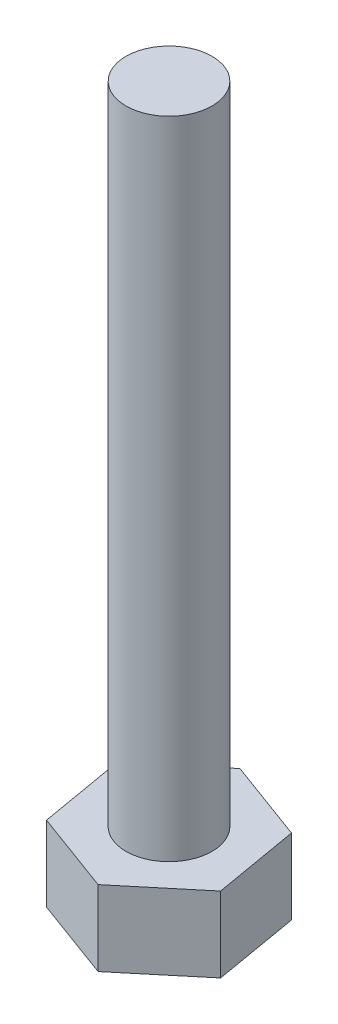
SolidWorks part; units mm, degrees
ref_plane "Спереди" through (0, 0, 0) normal (0, 0, 1) x (1, 0, 0)
ref_plane "Сверху" through (0, 0, 0) normal (0, 1, 0) x (1, 0, 0)
ref_plane "Справа" through (0, 0, 0) normal (1, 0, 0) x (0, 0, -1)
sketch "Эскиз1" plane through (0, 0, 0) normal (0, 1, 0) x (1, 0, 0)
  line L1 (3.7929, -1.3953) -> (3.1049, 2.5871)
  line L2 (3.1049, 2.5871) -> (-0.6881, 3.9824)
  line L3 (-0.6881, 3.9824) -> (-3.7929, 1.3953)
  line L4 (-3.7929, 1.3953) -> (-3.1049, -2.5871)
  line L5 (-3.1049, -2.5871) -> (0.6881, -3.9824)
  line L6 (0.6881, -3.9824) -> (3.7929, -1.3953)
  circle A0 centre (0, 0) radius 3.5 construction
  circle A1 centre (0, 0) radius 3.5 construction
  dimension "D1" = 7
extrude "Вытянуть1" add sketch "Эскиз1" along normal blind 3.5
sketch "Эскиз2" plane through (0, 3.5, 0) normal (0, 1, 0) x (1, 0, 0)
  circle A0 centre (0, 0) radius 2
  dimension "D1" = 4
extrude "Вытянуть2" add sketch "Эскиз2" along normal blind 30
